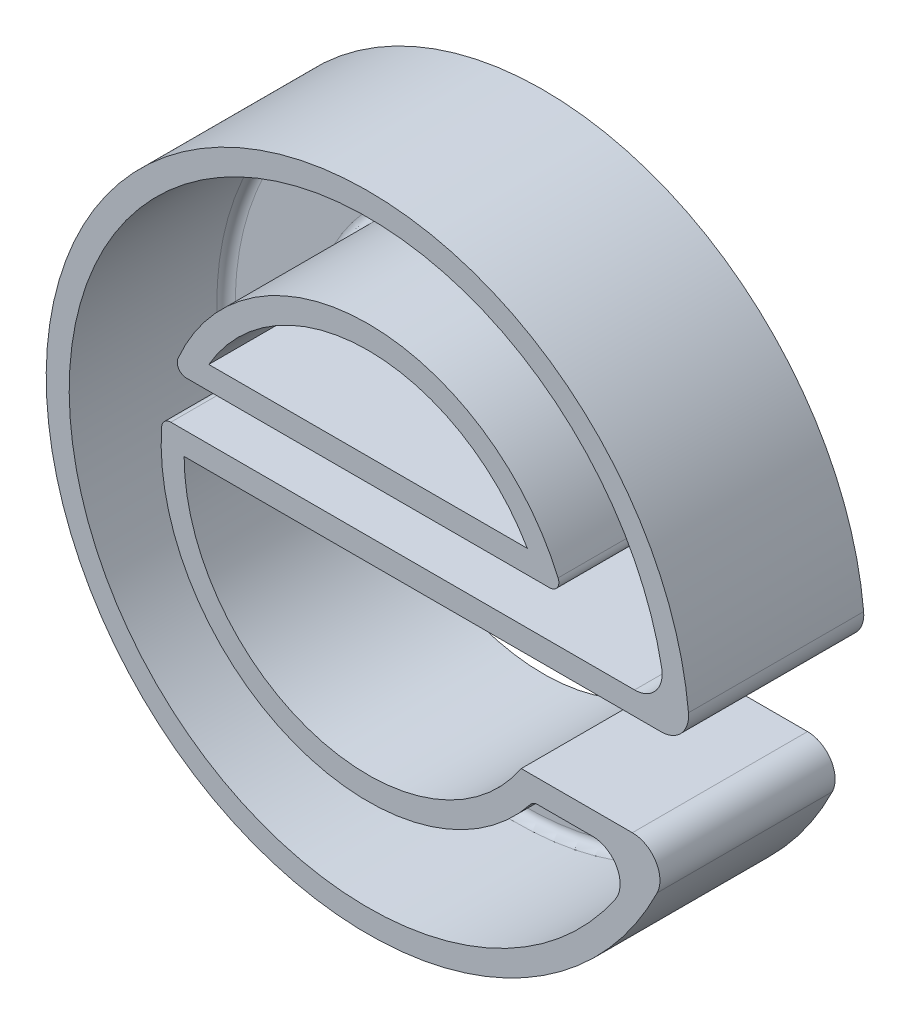
SolidWorks part; units mm, degrees
ref_plane "Alzado" through (0, 0, 0) normal (0, 0, 1) x (1, 0, 0)
ref_plane "Planta" through (0, 0, 0) normal (0, 1, 0) x (1, 0, 0)
ref_plane "Vista lateral" through (0, 0, 0) normal (1, 0, 0) x (0, 0, -1)
sketch "Sketch3" plane through (0, 0, 0) normal (0, 0, 1) x (1, 0, 0)
  line L0 (0, 0) -> (35, 0)
  line L1 (-17.3205, 10) -> (17.3205, 10)
  line L2 (16.6585, -11.0677) -> (33.204, -11.0677)
  line L3 (-20, 0) -> (0, 0)
  arc A0 (35, 0) -> (33.204, -11.0677) centre (0, 0) ccw
  arc A1 (17.3205, 10) -> (-17.3205, 10) centre (0, 0) ccw
  arc A2 (-20, 0) -> (16.6585, -11.0677) centre (0, 0) ccw
  point P1 (0, 0)
  point P9 (0, 0)
  dimension "D2" = 70
  dimension "D3" = 20
  dimension "D1" = 10
extrude "Boss-Extrude6" add sketch "Sketch3" along normal blind 19.05
sketch "Sketch6" plane through (0, 0, 19.05) normal (0, 0, 1) x (1, 0, 0)
  line L78 (17.3205, 10) -> (-17.3205, 10) construction
  line L79 (-20, 0) -> (20, 0) construction
  line L80 (20, 0) -> (35, 0) construction
  line L81 (33.204, -11.0677) -> (16.6585, -11.0677) construction
  line L82 (29.5325, -13.5677) -> (17.9491, -13.5677)
  line L83 (-22.3607, 2.5) -> (20, 2.5)
  line L84 (20, 2.5) -> (32.4037, 2.5)
  line L85 (21.2132, 7.5) -> (-21.2132, 7.5)
  arc A95 (35, 0) -> (33.204, -11.0677) centre (0, 0) ccw construction
  arc A96 (17.3205, 10) -> (-17.3205, 10) centre (0, 0) ccw construction
  arc A97 (-20, 0) -> (16.6585, -11.0677) centre (0, 0) ccw construction
  arc A98 (32.4037, 2.5) -> (29.5325, -13.5677) centre (0, 0) ccw
  arc A99 (-22.3607, 2.5) -> (17.9491, -13.5677) centre (0, 0) ccw
  arc A100 (21.2132, 7.5) -> (-21.2132, 7.5) centre (0, 0) ccw
  dimension "D1" = 2.5
  dimension "D2" = 2.5
extrude "Cut-Extrude2" cut sketch "Sketch6" against normal blind 17.05
fillet "Fillet2" radius 3 4 edges at (32.4037, 2.5, 10.525) (35, 0, 9.525) (33.204, -11.0677, 9.525) (29.5325, -13.5677, 10.525)
fillet "Fillet1" radius 1 12 edges at (0, 7.5, 2) (0, 22.5, 2) (3.311, 2.5, 2) (21.1787, -13.5677, 2) (-8.3311, -20.9008, 2) (-31.8234, 6.5968, 2) (-21.2132, 7.5, 10.525) (21.2132, 7.5, 10.525) (-22.3607, 2.5, 10.525) (17.9491, -13.5677, 10.525) (31.2934, 3.5866, 2) (27.0591, -15.1631, 2)
